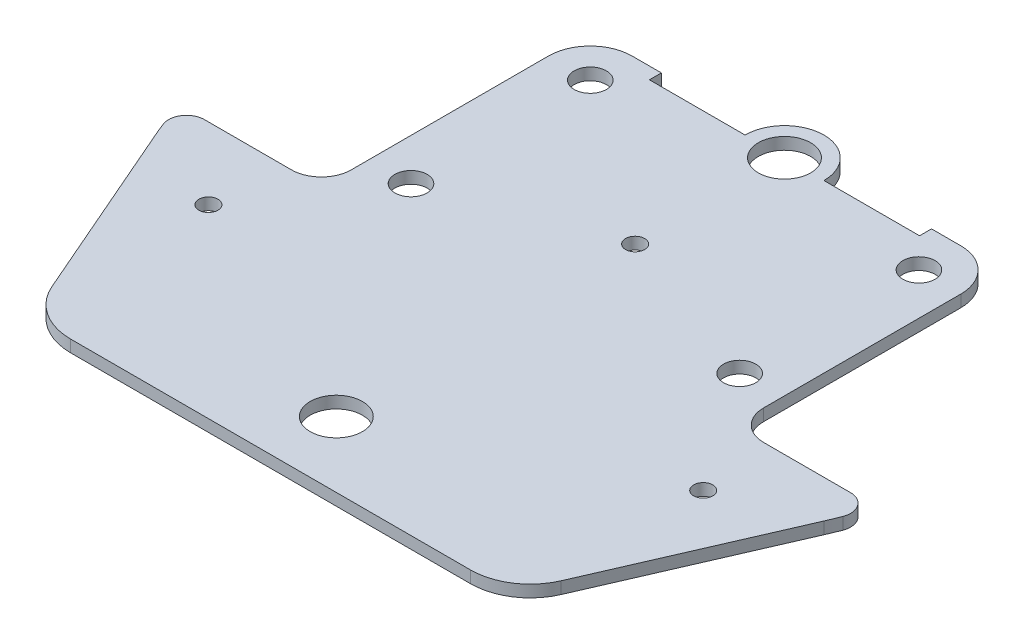
SolidWorks part; units mm, degrees
ref_plane "Front Plane" through (0, 0, 0) normal (0, 0, 1) x (1, 0, 0)
ref_plane "Top Plane" through (0, 0, 0) normal (0, 1, 0) x (1, 0, 0)
ref_plane "Right Plane" through (0, 0, 0) normal (1, 0, 0) x (0, 0, -1)
sketch "Sketch1" plane through (0, 0, 0) normal (0, 1, 0) x (1, 0, 0)
  line L0 (0, 61) -> (0, -61) construction
  line L1 (-61, 0) -> (61, 0) construction
  line L2 (-27.5, 20) -> (-27.5, -10) construction
  line L3 (-20.5, 20) -> (-20.5, -10)
  line L4 (-34.5, 20) -> (-34.5, -10)
  line L5 (27.5, 20) -> (27.5, -10) construction
  line L6 (20.5, 20) -> (20.5, -10)
  line L7 (34.5, 20) -> (34.5, -10)
  line L8 (-6.601, 25) -> (-22.601, 25)
  line L9 (6.601, 25) -> (22.601, 25)
  line L10 (-34.5, -10) -> (-34.5, -50.3066)
  line L11 (34.5, -10) -> (34.5, -50.3066)
  line L12 (-27.5, 27) -> (-22.601, 27)
  line L13 (-22.601, 27) -> (-22.601, 25)
  line L14 (-27.5, 16.6282) -> (-27.5, -15.3718) construction
  line L15 (27.5, 16.6282) -> (27.5, -15.3718) construction
  line L16 (22.601, 25) -> (22.601, 27)
  line L17 (22.601, 27) -> (27.5, 27)
  line L18 (-6.601, 25) -> (-6.601, 27)
  line L19 (-6.601, 27) -> (6.601, 27)
  line L20 (6.601, 27) -> (6.601, 25)
  line L21 (-6.601, 25) -> (6.601, 25) construction
  circle A0 centre (0, 0) radius 61
  circle A1 centre (-27.5, 20) radius 2.7
  circle A2 centre (-27.5, -10) radius 2.7
  circle A3 centre (27.5, -10) radius 2.7
  circle A4 centre (27.5, 20) radius 2.7
  circle A5 centre (0, 25) radius 6.601
  arc A6 (-20.5, 20) -> (-34.5, 20) centre (-27.5, 20) ccw
  arc A7 (-34.5, -10) -> (-20.5, -10) centre (-27.5, -10) ccw
  arc A8 (20.5, 20) -> (34.5, 20) centre (27.5, 20) cw
  arc A9 (34.5, -10) -> (20.5, -10) centre (27.5, -10) cw
  point P7 (-45.5, 0)
  point P8 (-27.5, 5)
  point P15 (27.5, 5)
  point P46 (-22.601, 26)
  point P49 (-6.601, 26)
  point P50 (22.601, 26)
  dimension "D1" = 122
  dimension "D5" = 5.4
  dimension "D6" = 5.4
  dimension "D7" = 20
  dimension "D8" = 10
  dimension "D4" = 7
  dimension "D2" = 2
  dimension "D9" = 55
  dimension "D10" = 16
  dimension "D11" = 16
extrude "Boss-Extrude1" add sketch "Sketch1" along normal blind 2 contours L4 A7 L3 A6 A1 A2 | L11 A9 L6 A8 L9 A5 L8 A6 L3 A7 L10 A0 | A9 L7 A8 L6 A3 A4 | A5 L19 | L19 A5 | A6 L13 L12 | L16 A8 L17
sketch "Sketch5" plane through (0, 2, 0) normal (0, 1, 0) x (1, 0, 0)
  line L0 (0, 0) -> (0, -72.0784) construction
  line L1 (-40, -61) -> (40, -61)
  line L2 (40, -61) -> (55.9444, -24.3152)
  line L3 (0, 0) -> (55.9444, -24.3152) construction
  line L4 (-40, -61) -> (-55.9444, -24.3152)
  line L5 (-58.6891, -18) -> (-39.5, -18)
  line L6 (-34.5, 0) -> (-34.5, -13)
  line L7 (-34.5, 20) -> (-34.5, -50.3066) construction
  line L8 (34.5, 0) -> (34.5, -13)
  line L9 (34.5, 20) -> (34.5, -50.3066) construction
  line L10 (-58.6891, -18) -> (67.7303, -18) construction
  line L11 (58.2838, -18) -> (39.5, -18)
  line L12 (-34.5, -13) -> (-34.5, -50.3066)
  line L13 (34.5, -16.4218) -> (34.5, -50.3066)
  line L14 (34.5, -18) -> (34.5, -3.8977)
  circle A0 centre (0, 0) radius 61
  arc A1 (-34.5, -13) -> (-39.5, -18) centre (-39.5, -13) cw
  arc A2 (39.5, -18) -> (34.5, -13) centre (39.5, -13) cw
  point P9 (0, -61)
  dimension "D2" = 122
  dimension "D5" = 5
  dimension "D6" = 5
  dimension "D1" = 40
  dimension "D3" = 90
  dimension "D4" = 43
extrude "Boss-Extrude2" add sketch "Sketch5" against normal blind 2
fillet "Fillet1" radius 3 2 edges at (-58.2838, 1, 18) (58.2838, 1, 18)
sketch "Sketch2" plane through (0, 2, 0) normal (0, 1, 0) x (1, 0, 0)
  line L0 (0, 35.2971) -> (0, -61) construction
  line L1 (-31.8075, 0) -> (31.8075, 0) construction
  line L2 (-55.4131, -30) -> (57.2638, -30) construction
  line L3 (-40, -61) -> (40, -61) construction
  circle A2 centre (0, 25) radius 4.375
  circle A3 centre (0, -50) radius 4.375
  circle A4 centre (0, 0) radius 1.6
  circle A5 centre (-41.4, -30) radius 1.6
  circle A6 centre (41.4, -30) radius 1.6
  point P4 (0, 0)
  point P5 (0, 0)
  dimension "D1" = 8.75
  dimension "D2" = 8.75
  dimension "D3" = 50
  dimension "D4" = 3.2
  dimension "D6" = 41.4
  dimension "D7" = 3.2
  dimension "D5" = 30
extrude "Cut-Extrude1" cut sketch "Sketch2" against normal through all
fillet "Fillet2" radius 10 2 edges at (40, 1, 61) (-40, 1, 61)
